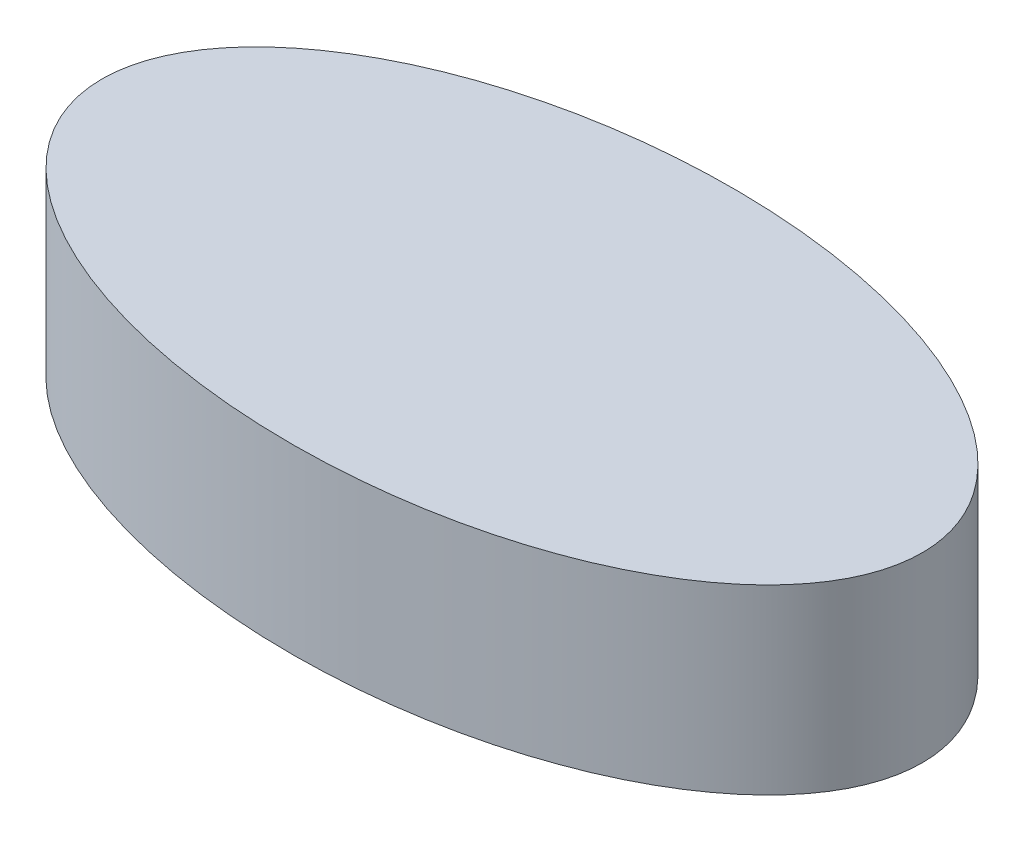
SolidWorks part; units mm, degrees
ref_plane "Front Plane" through (0, 0, 0) normal (0, 0, 1) x (1, 0, 0)
ref_plane "Top Plane" through (0, 0, 0) normal (0, 1, 0) x (1, 0, 0)
ref_plane "Right Plane" through (0, 0, 0) normal (1, 0, 0) x (0, 0, -1)
sketch "Sketch1" plane through (0, 0, 0) normal (0, 1, 0) x (1, 0, 0)
  ellipse E0 centre (0, 0) end of major axis (-338.1787, 0) minor radius 182.2594
  point P1 (277.8633, 0)
  point P7 (0, 158.4731)
  point P9 (323.737, 0)
  point P10 (0, 182.2594)
  point P11 (338.1787, 0)
extrude "Boss-Extrude1" add sketch "Sketch1" along normal blind 150
ref_plane "Plane1" through (162.6, 0, 0) normal (1, 0, 0) x (0, 0, -1)
sketch "Sketch3" plane through (162.6, 0, 0) normal (1, 0, 0) x (0, 0, -1)
  line L0 (0, 0) -> (0, 60)
  line L1 (-182.2594, 0) -> (182.2594, 0) construction
  line L2 (60, 0) -> (0, 0)
  arc A0 (0, 60) -> (60, 0) centre (0, 0) cw
  dimension "D1" = 60
  dimension "D2" = 60
revolve "Cut-Revolve2" cut sketch "Sketch3" angle 360 about L0
sketch "Sketch4" plane through (0, 150, 0) normal (0, 1, 0) x (1, 0, 0)
  ellipse E0 centre (0, 0) end of major axis (-338.1787, 0) minor radius 182.2594 construction
  point P0 (0, -182.2594)
  point P1 (338.1787, 0)
  point P8 (0, 182.2594)
  point P9 (-338.1787, 0)
ref_plane "Plane2" through (-162.6, 0, 0) normal (1, 0, 0) x (0, 0, -1)
sketch "Sketch5" plane through (-162.6, 0, 0) normal (1, 0, 0) x (0, 0, -1)
  line L0 (0, 0) -> (0, 60)
  line L1 (60, 0) -> (0, 0)
  arc A0 (0, 60) -> (60, 0) centre (0, 0) cw
  dimension "D1" = 60
  dimension "D2" = 60
revolve "Cut-Revolve3" cut sketch "Sketch5" angle 360 about L0
